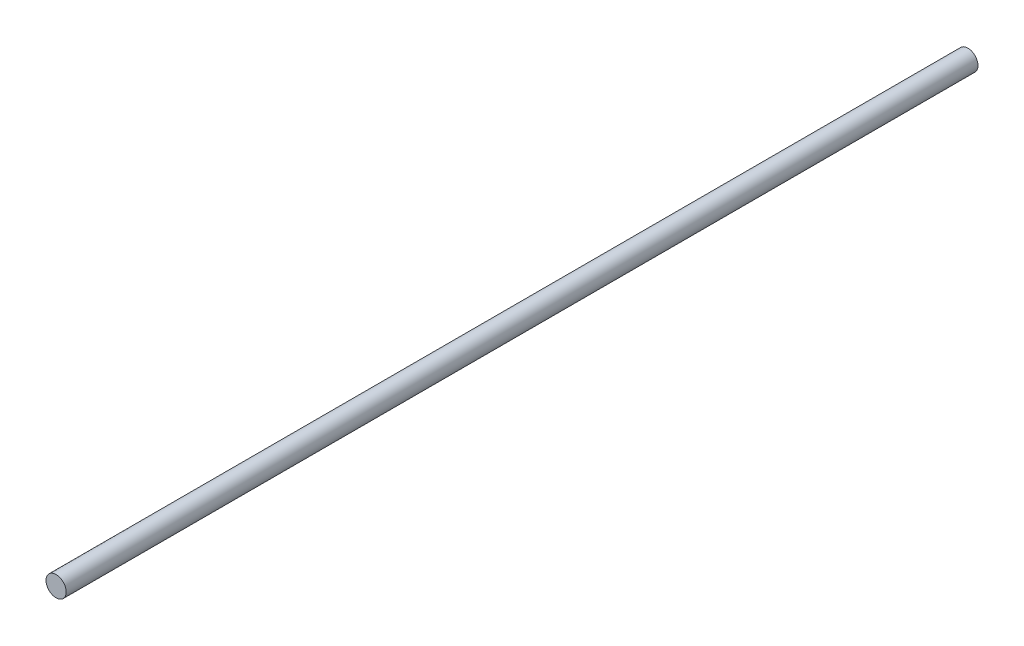
SolidWorks part; units mm, degrees
ref_plane "Ebene vorne" through (0, 0, 0) normal (0, 0, 1) x (1, 0, 0)
ref_plane "Ebene oben" through (0, 0, 0) normal (0, 1, 0) x (1, 0, 0)
ref_plane "Ebene rechts" through (0, 0, 0) normal (1, 0, 0) x (0, 0, -1)
sketch "Skizze1" plane through (0, 0, 0) normal (0, 0, 1) x (1, 0, 0)
  circle A0 centre (0, 0) radius 3.325
  dimension "D1" = 6.65
extrude "Aufsatz-Linear austragen1" add sketch "Skizze1" along normal blind 300
cosmetic thread "Gewindedarstellung1"
